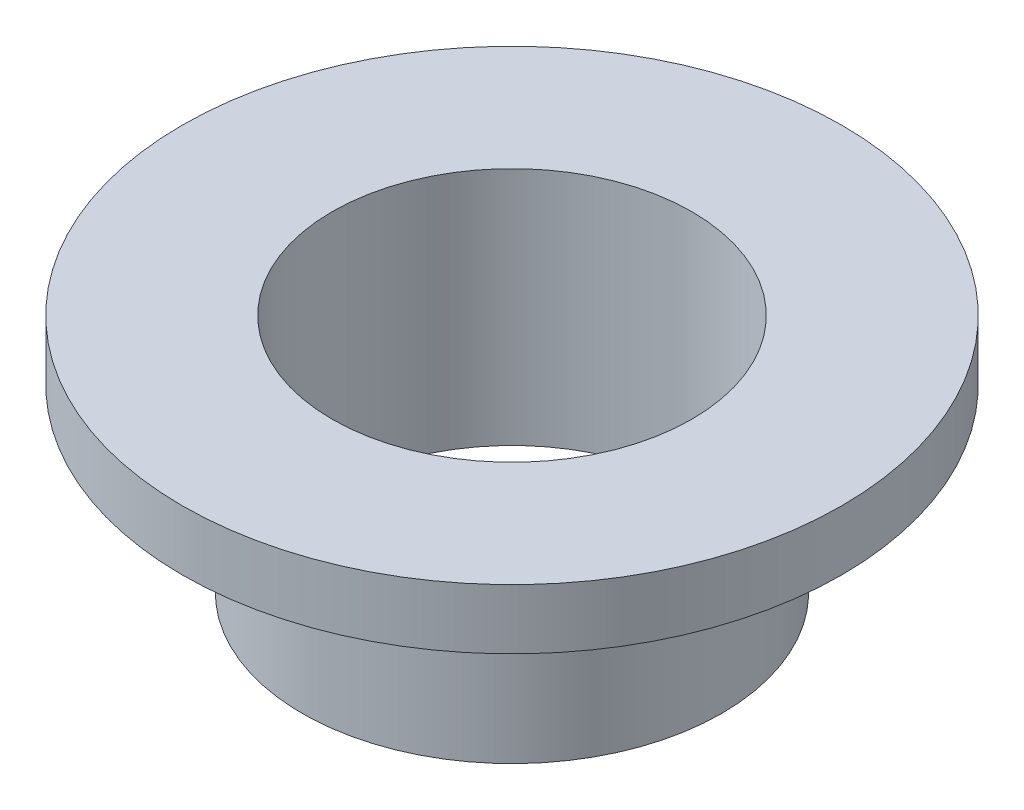
SolidWorks part; units mm, degrees
ref_plane "Front Plane" through (0, 0, 0) normal (0, 0, 1) x (1, 0, 0)
ref_plane "Top Plane" through (0, 0, 0) normal (0, 1, 0) x (1, 0, 0)
ref_plane "Right Plane" through (0, 0, 0) normal (1, 0, 0) x (0, 0, -1)
sketch "Sketch1" plane through (0, 0, 0) normal (0, 0, 1) x (1, 0, 0)
  line L0 (3, 0) -> (5.5, 0)
  line L1 (5.5, 0) -> (5.5, -1)
  line L2 (5.5, -1) -> (3.5, -1)
  line L3 (3.5, -1) -> (3.5, -4)
  line L4 (3.5, -4) -> (3, -4)
  line L5 (3, -4) -> (3, 0)
  line L6 (0, 0) -> (0, -9.4735) construction
  dimension "D1" = 3
  dimension "D2" = 3.5
  dimension "D3" = 4
  dimension "D4" = 1
  dimension "D5" = 5.5
revolve "Revolve1" add sketch "Sketch1" angle 360 about L6
